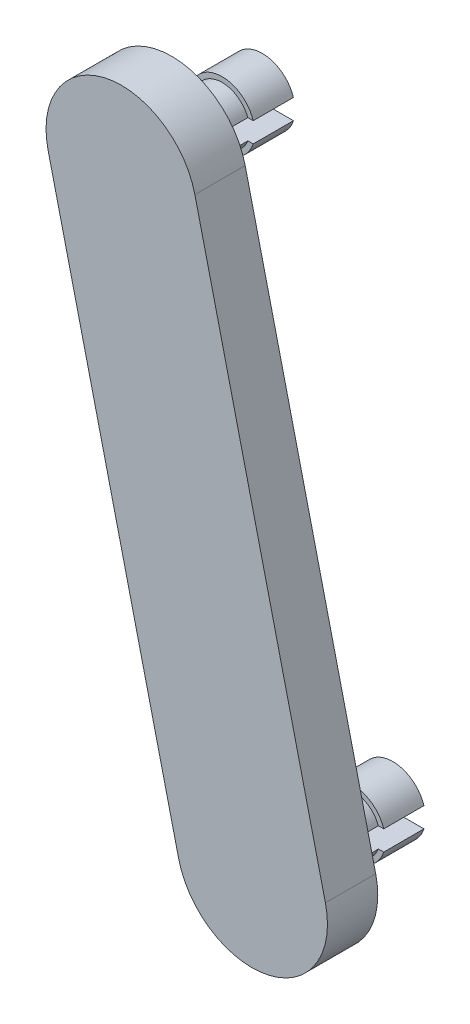
SolidWorks part; units mm, degrees
ref_plane "Plan de face" through (0, 0, 0) normal (0, 0, 1) x (1, 0, 0)
ref_plane "Plan de dessus" through (0, 0, 0) normal (0, 1, 0) x (1, 0, 0)
ref_plane "Plan de droite" through (0, 0, 0) normal (1, 0, 0) x (0, 0, -1)
sketch "Esquisse1" plane through (0, 0, 0) normal (0, 0, 1) x (1, 0, 0)
  line L0 (-104.5852, -42.1267) -> (-117.5602, 12.3494) construction
  line L1 (-111.8811, -43.8644) -> (-124.8561, 10.6117)
  line L2 (-97.2892, -40.389) -> (-110.2643, 14.0872)
  arc A0 (-111.8811, -43.8644) -> (-97.2892, -40.389) centre (-104.5852, -42.1267) ccw
  arc A1 (-110.2643, 14.0872) -> (-124.8561, 10.6117) centre (-117.5602, 12.3494) ccw
  point P4 (-111.0727, -14.8886)
  dimension "D1" = 15
extrude "Boss.-Extru.1" add sketch "Esquisse1" along normal blind 5
sketch "Esquisse3" plane through (0, 0, 0) normal (0, 0, 1) x (1, 0, 0)
  circle A0 centre (-117.5602, 12.3494) radius 2.75
  circle A1 centre (-104.5852, -42.1267) radius 2.75
  dimension "D1" = 5.5
  dimension "D2" = 5.5
extrude "Boss.-Extru.2" add sketch "Esquisse3" against normal blind 5
sketch "Esquisse4" plane through (0, 0, -5) normal (0, 0, -1) x (-1, 0, 0)
  circle A0 centre (117.5602, 12.3494) radius 3.25
  circle A1 centre (104.5852, -42.1267) radius 3.25
  dimension "D1" = 6.5
  dimension "D2" = 6.5
extrude "Boss.-Extru.3" add sketch "Esquisse4" along normal blind 4
sketch "Esquisse5" plane through (0, 0, -9) normal (0, 0, -1) x (-1, 0, 0)
  line L1 (99.5852, -41.1267) -> (109.5852, -41.1267)
  line L2 (99.5852, -41.1267) -> (99.5852, -43.1267)
  line L3 (99.5852, -43.1267) -> (109.5852, -43.1267)
  line L4 (109.5852, -41.1267) -> (109.5852, -43.1267)
  line L5 (112.5602, 13.3494) -> (122.5602, 13.3494)
  line L6 (112.5602, 13.3494) -> (112.5602, 11.3494)
  line L7 (112.5602, 11.3494) -> (122.5602, 11.3494)
  line L8 (122.5602, 13.3494) -> (122.5602, 11.3494)
  dimension "D1" = 1
  dimension "D2" = 1
  dimension "D3" = 10
  dimension "D4" = 5
  dimension "D5" = 1
  dimension "D6" = 1
  dimension "D7" = 10
  dimension "D8" = 5
extrude "Enlèv. mat.-Extru.1" cut sketch "Esquisse5" against normal blind 9
